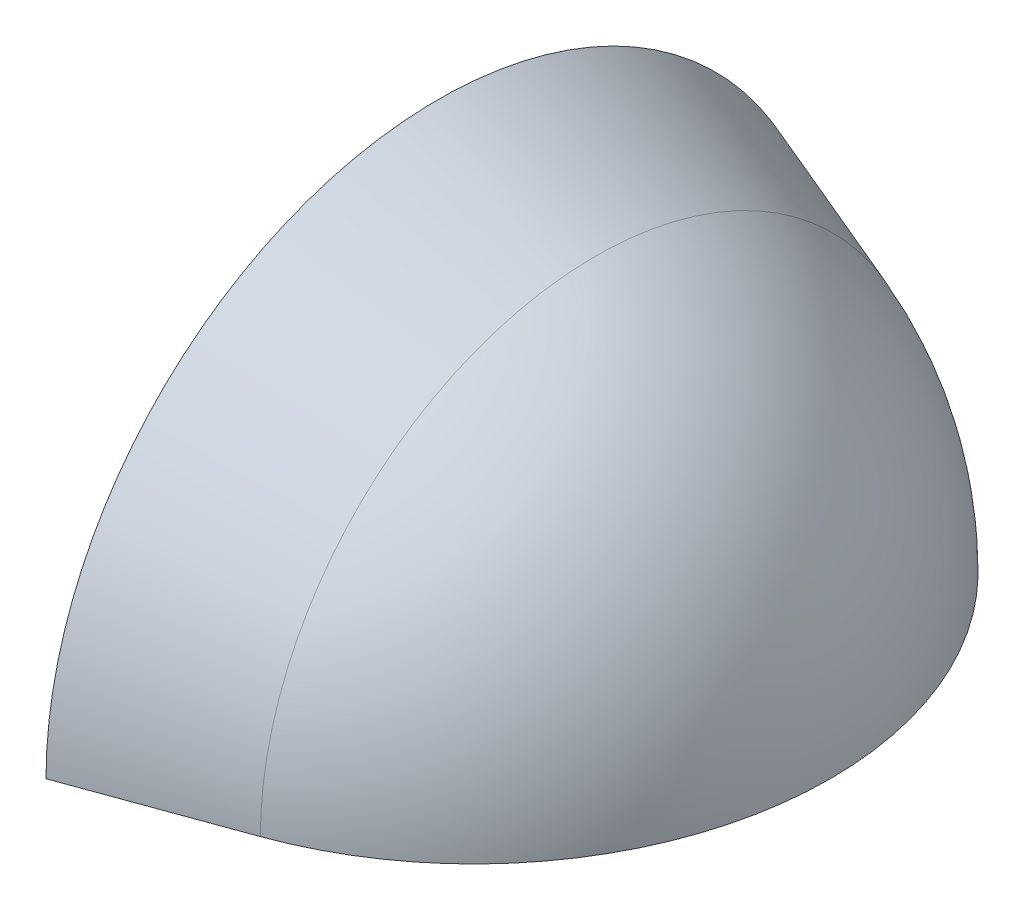
SolidWorks part; units mm, degrees
ref_plane "Front Plane" through (0, 0, 0) normal (0, 0, 1) x (1, 0, 0)
ref_plane "Top Plane" through (0, 0, 0) normal (0, 1, 0) x (1, 0, 0)
ref_plane "Right Plane" through (0, 0, 0) normal (1, 0, 0) x (0, 0, -1)
sketch "Sketch1" plane through (0, 0, 0) normal (0, 0, 1) x (1, 0, 0)
  line L0 (-25.4, 0) -> (-25.4, 25.4)
  line L1 (0, 0) -> (-25.4, 0) construction
  line L5 (-25.4, 25.4) -> (-15.2137, 21.7041)
  line L6 (0, 0) -> (-25.4, 0)
  arc A0 (0, 0) -> (-15.2137, 21.7041) centre (-23.0886, 0) ccw
  dimension "D1" = 25.4
  dimension "D2" = 25.4
revolve "Revolve1" add sketch "Sketch1" angle 360 about L6
sketch "Sketch2" plane through (0, 0, 0) normal (0, 0, 1) x (1, 0, 0)
  line L5 (7.8373, 0) -> (-82.7974, 0)
  line L6 (-82.7974, 0) -> (-82.7974, -32.536)
  line L7 (-82.7974, -32.536) -> (7.8373, -32.536)
  line L8 (7.8373, -32.536) -> (7.8373, 0)
extrude "Cut-Extrude5" cut sketch "Sketch2" against normal through all and the other way through all
